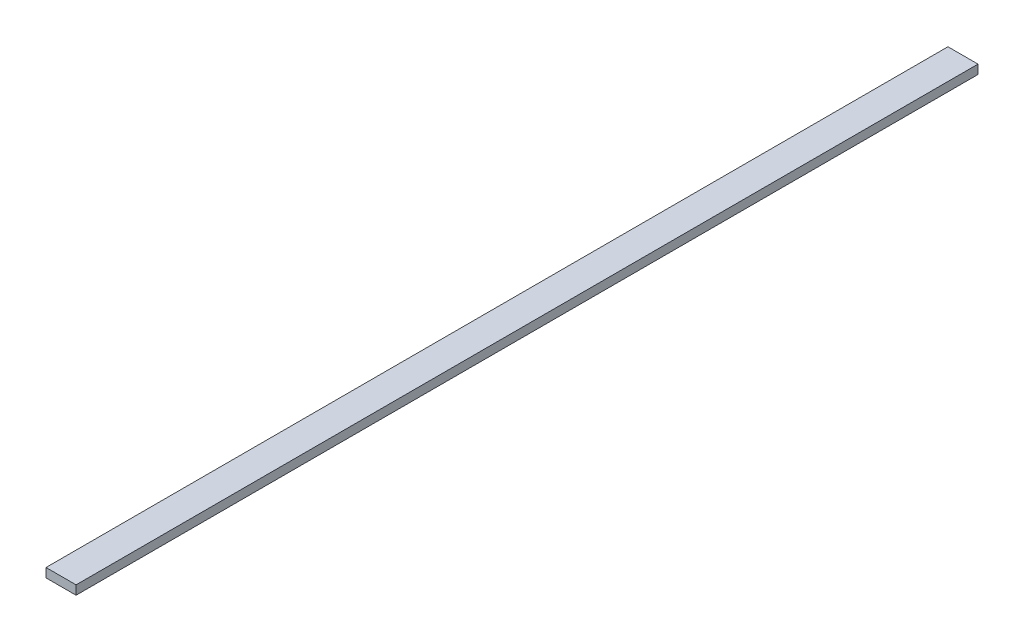
SolidWorks part; units mm, degrees
ref_plane "前视基准面" through (0, 0, 0) normal (0, 0, 1) x (1, 0, 0)
ref_plane "上视基准面" through (0, 0, 0) normal (0, 1, 0) x (1, 0, 0)
ref_plane "右视基准面" through (0, 0, 0) normal (1, 0, 0) x (0, 0, -1)
other "Configuration Table"
sketch "草图1" plane through (0, 0, 0) normal (0, 1, 0) x (1, 0, 0)
  line L1 (-23.6538, 47.6996) -> (-13.6538, 47.6996)
  line L2 (-23.6538, 47.6996) -> (-23.6538, -252.3004)
  line L3 (-23.6538, -252.3004) -> (-13.6538, -252.3004)
  line L4 (-13.6538, 47.6996) -> (-13.6538, -252.3004)
  dimension "D1" = 300
  dimension "D2" = 10
extrude "凸台-拉伸1" add sketch "草图1" along normal blind 3
